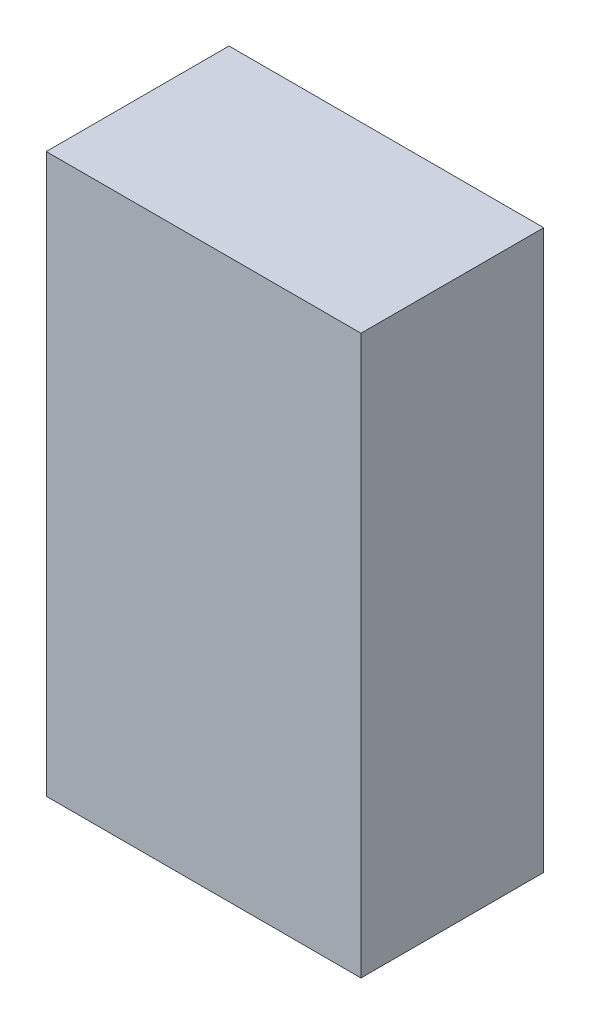
SolidWorks part; units mm, degrees
ref_plane "Front Plane" through (0, 0, 0) normal (0, 0, 1) x (1, 0, 0)
ref_plane "Top Plane" through (0, 0, 0) normal (0, 1, 0) x (1, 0, 0)
ref_plane "Right Plane" through (0, 0, 0) normal (1, 0, 0) x (0, 0, -1)
sketch "Sketch1" plane through (0, 0, 0) normal (0, 1, 0) x (1, 0, 0)
  line L1 (-15.5, 9) -> (15.5, 9)
  line L2 (-15.5, 9) -> (-15.5, -9)
  line L3 (-15.5, -9) -> (15.5, -9)
  line L4 (15.5, 9) -> (15.5, -9)
  line L5 (-15.5, 9) -> (15.5, -9) construction
  line L6 (-15.5, -9) -> (15.5, 9) construction
  point P4 (0, 0)
  point P5 (0, 0)
  dimension "D1" = 31
  dimension "D2" = 18
extrude "Boss-Extrude1" add sketch "Sketch1" along normal blind 55
